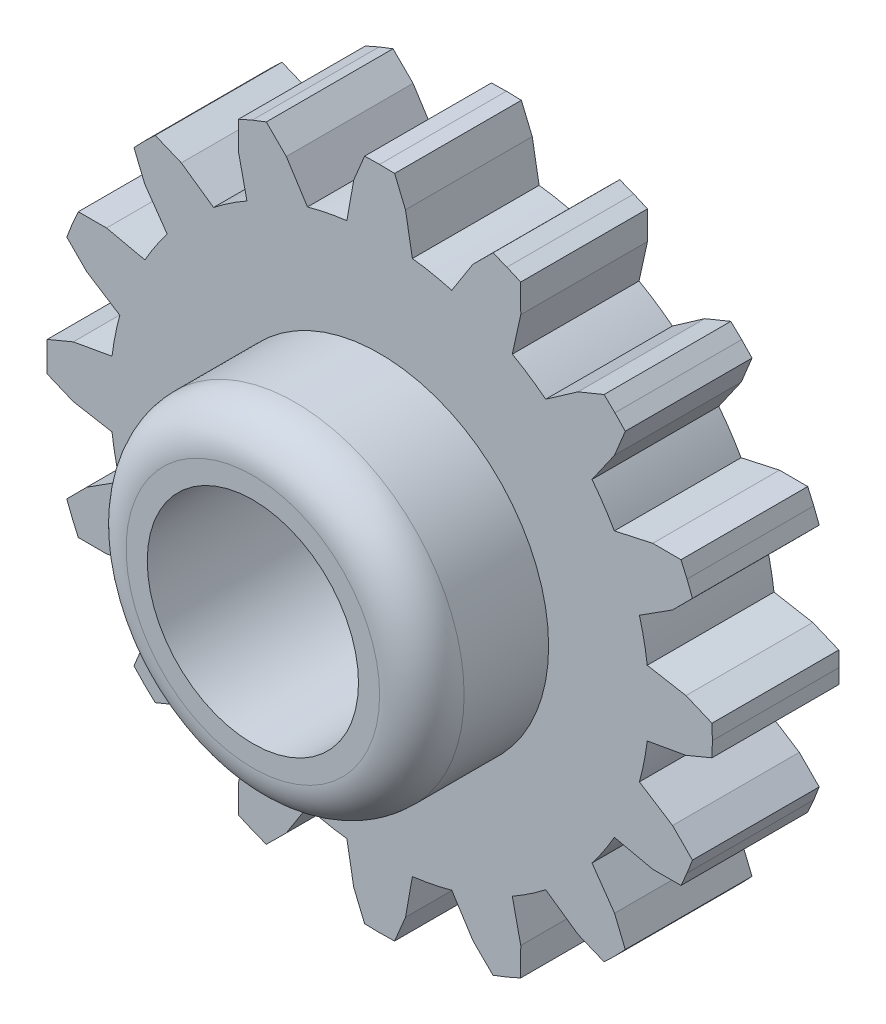
SolidWorks part; units mm, degrees
material "Chrome Stainless Steel"
ref_plane "Front Plane" through (0, 0, 0) normal (0, 0, 1) x (1, 0, 0)
ref_plane "Top Plane" through (0, 0, 0) normal (0, 1, 0) x (1, 0, 0)
ref_plane "Right Plane" through (0, 0, 0) normal (1, 0, 0) x (0, 0, -1)
sketch "Sketch1" plane through (0, 0, 0) normal (0, 0, 1) x (1, 0, 0)
  line L0 (0, 6.3811) -> (0, 7.875) construction
  line L1 (-0.7753, 6.3338) -> (-0.6124, 7.2503)
  line L2 (-0.6124, 7.2503) -> (-0.3549, 7.867)
  line L3 (-0.3549, 7.867) -> (0, 7.875)
  line L4 (0.3549, 7.867) -> (0, 7.875)
  line L5 (0.7753, 6.3338) -> (0.6124, 7.2503)
  line L6 (0.6124, 7.2503) -> (0.3549, 7.867)
  line L7 (1.7075, 6.1484) -> (2.2088, 6.9328)
  line L8 (2.2088, 6.9328) -> (2.6827, 7.404)
  line L9 (2.6827, 7.404) -> (3.0136, 7.2756)
  line L10 (3.3385, 7.1323) -> (3.0136, 7.2756)
  line L11 (3.1401, 5.555) -> (3.3403, 6.4641)
  line L12 (3.3403, 6.4641) -> (3.3385, 7.1323)
  line L13 (2.4419, 5.8954) -> (3.0136, 7.2756) construction
  line L14 (3.9305, 5.0269) -> (4.6937, 5.5598)
  line L15 (4.6937, 5.5598) -> (5.3118, 5.8138)
  line L16 (5.3118, 5.8138) -> (5.5685, 5.5685)
  line L17 (5.8138, 5.3118) -> (5.5685, 5.5685)
  line L18 (5.0269, 3.9305) -> (5.5598, 4.6937)
  line L19 (5.5598, 4.6937) -> (5.8138, 5.3118)
  line L20 (4.5121, 4.5121) -> (5.5685, 5.5685) construction
  line L21 (5.555, 3.1401) -> (6.4641, 3.3403)
  line L22 (6.4641, 3.3403) -> (7.1323, 3.3385)
  line L23 (7.1323, 3.3385) -> (7.2756, 3.0136)
  line L24 (7.404, 2.6827) -> (7.2756, 3.0136)
  line L25 (6.1484, 1.7075) -> (6.9328, 2.2088)
  line L26 (6.9328, 2.2088) -> (7.404, 2.6827)
  line L27 (5.8954, 2.4419) -> (7.2756, 3.0136) construction
  line L28 (6.3338, 0.7753) -> (7.2503, 0.6124)
  line L29 (7.2503, 0.6124) -> (7.867, 0.3549)
  line L30 (7.867, 0.3549) -> (7.875, 0)
  line L31 (7.867, -0.3549) -> (7.875, 0)
  line L32 (6.3338, -0.7753) -> (7.2503, -0.6124)
  line L33 (7.2503, -0.6124) -> (7.867, -0.3549)
  line L34 (6.3811, 0) -> (7.875, 0) construction
  line L35 (6.1484, -1.7075) -> (6.9328, -2.2088)
  line L36 (6.9328, -2.2088) -> (7.404, -2.6827)
  line L37 (7.404, -2.6827) -> (7.2756, -3.0136)
  line L38 (7.1323, -3.3385) -> (7.2756, -3.0136)
  line L39 (5.555, -3.1401) -> (6.4641, -3.3403)
  line L40 (6.4641, -3.3403) -> (7.1323, -3.3385)
  line L41 (5.8954, -2.4419) -> (7.2756, -3.0136) construction
  line L42 (5.0269, -3.9305) -> (5.5598, -4.6937)
  line L43 (5.5598, -4.6937) -> (5.8138, -5.3118)
  line L44 (5.8138, -5.3118) -> (5.5685, -5.5685)
  line L45 (5.3118, -5.8138) -> (5.5685, -5.5685)
  line L46 (3.9305, -5.0269) -> (4.6937, -5.5598)
  line L47 (4.6937, -5.5598) -> (5.3118, -5.8138)
  line L48 (4.5121, -4.5121) -> (5.5685, -5.5685) construction
  line L49 (3.1401, -5.555) -> (3.3403, -6.4641)
  line L50 (3.3403, -6.4641) -> (3.3385, -7.1323)
  line L51 (3.3385, -7.1323) -> (3.0136, -7.2756)
  line L52 (2.6827, -7.404) -> (3.0136, -7.2756)
  line L53 (1.7075, -6.1484) -> (2.2088, -6.9328)
  line L54 (2.2088, -6.9328) -> (2.6827, -7.404)
  line L55 (2.4419, -5.8954) -> (3.0136, -7.2756) construction
  line L56 (0.7753, -6.3338) -> (0.6124, -7.2503)
  line L57 (0.6124, -7.2503) -> (0.3549, -7.867)
  line L58 (0.3549, -7.867) -> (0, -7.875)
  line L59 (-0.3549, -7.867) -> (0, -7.875)
  line L60 (-0.7753, -6.3338) -> (-0.6124, -7.2503)
  line L61 (-0.6124, -7.2503) -> (-0.3549, -7.867)
  line L62 (0, -6.3811) -> (0, -7.875) construction
  line L63 (-1.7075, -6.1484) -> (-2.2088, -6.9328)
  line L64 (-2.2088, -6.9328) -> (-2.6827, -7.404)
  line L65 (-2.6827, -7.404) -> (-3.0136, -7.2756)
  line L66 (-3.3385, -7.1323) -> (-3.0136, -7.2756)
  line L67 (-3.1401, -5.555) -> (-3.3403, -6.4641)
  line L68 (-3.3403, -6.4641) -> (-3.3385, -7.1323)
  line L69 (-2.4419, -5.8954) -> (-3.0136, -7.2756) construction
  line L70 (-3.9305, -5.0269) -> (-4.6937, -5.5598)
  line L71 (-4.6937, -5.5598) -> (-5.3118, -5.8138)
  line L72 (-5.3118, -5.8138) -> (-5.5685, -5.5685)
  line L73 (-5.8138, -5.3118) -> (-5.5685, -5.5685)
  line L74 (-5.0269, -3.9305) -> (-5.5598, -4.6937)
  line L75 (-5.5598, -4.6937) -> (-5.8138, -5.3118)
  line L76 (-4.5121, -4.5121) -> (-5.5685, -5.5685) construction
  line L77 (-5.555, -3.1401) -> (-6.4641, -3.3403)
  line L78 (-6.4641, -3.3403) -> (-7.1323, -3.3385)
  line L79 (-7.1323, -3.3385) -> (-7.2756, -3.0136)
  line L80 (-7.404, -2.6827) -> (-7.2756, -3.0136)
  line L81 (-6.1484, -1.7075) -> (-6.9328, -2.2088)
  line L82 (-6.9328, -2.2088) -> (-7.404, -2.6827)
  line L83 (-5.8954, -2.4419) -> (-7.2756, -3.0136) construction
  line L84 (-6.3338, -0.7753) -> (-7.2503, -0.6124)
  line L85 (-7.2503, -0.6124) -> (-7.867, -0.3549)
  line L86 (-7.867, -0.3549) -> (-7.875, 0)
  line L87 (-7.867, 0.3549) -> (-7.875, 0)
  line L88 (-6.3338, 0.7753) -> (-7.2503, 0.6124)
  line L89 (-7.2503, 0.6124) -> (-7.867, 0.3549)
  line L90 (-6.3811, 0) -> (-7.875, 0) construction
  line L91 (-6.1484, 1.7075) -> (-6.9328, 2.2088)
  line L92 (-6.9328, 2.2088) -> (-7.404, 2.6827)
  line L93 (-7.404, 2.6827) -> (-7.2756, 3.0136)
  line L94 (-7.1323, 3.3385) -> (-7.2756, 3.0136)
  line L95 (-5.555, 3.1401) -> (-6.4641, 3.3403)
  line L96 (-6.4641, 3.3403) -> (-7.1323, 3.3385)
  line L97 (-5.8954, 2.4419) -> (-7.2756, 3.0136) construction
  line L98 (-5.0269, 3.9305) -> (-5.5598, 4.6937)
  line L99 (-5.5598, 4.6937) -> (-5.8138, 5.3118)
  line L100 (-5.8138, 5.3118) -> (-5.5685, 5.5685)
  line L101 (-5.3118, 5.8138) -> (-5.5685, 5.5685)
  line L102 (-3.9305, 5.0269) -> (-4.6937, 5.5598)
  line L103 (-4.6937, 5.5598) -> (-5.3118, 5.8138)
  line L104 (-4.5121, 4.5121) -> (-5.5685, 5.5685) construction
  line L105 (-3.1401, 5.555) -> (-3.3403, 6.4641)
  line L106 (-3.3403, 6.4641) -> (-3.3385, 7.1323)
  line L107 (-3.3385, 7.1323) -> (-3.0136, 7.2756)
  line L108 (-2.6827, 7.404) -> (-3.0136, 7.2756)
  line L109 (-1.7075, 6.1484) -> (-2.2088, 6.9328)
  line L110 (-2.2088, 6.9328) -> (-2.6827, 7.404)
  line L111 (-2.4419, 5.8954) -> (-3.0136, 7.2756) construction
  circle A0 centre (0, 0) radius 6.3811
  circle A1 centre (0, 0) radius 7.875
  circle A2 centre (0, 0) radius 2.5
  point P135 (0, 0)
  point P166 (0, 0)
  point P246 (0, 0)
  dimension "D1" = 15.75
  dimension "D2" = 5
  dimension "D3" = 0.3549
  dimension "D4" = 0.6682
  dimension "D5" = 3.0136
  dimension "D6" = 1.6277
  dimension "D8" = 0.9309
  dimension "D9" = 167.42
  dimension "D10" = 42.661
  dimension "D7" = 16
extrude "Boss-Extrude3" add sketch "Sketch1" along normal blind 3 contours A0 | A0 L11 L12 L10 L9 L8 L7 | A0 L5 L6 L4 L3 L2 L1 | A0 L109 L110 L108 L107 L106 L105 | A0 L102 L103 L101 L100 L99 L98 | A0 L95 L96 L94 L93 L92 L91 | A0 L88 L89 L87 L86 L85 L84 | A0 L81 L82 L80 L79 L78 L77 | A0 L74 L75 L73 L72 L71 L70 | A0 L67 L68 L66 L65 L64 L63 | A0 L60 L61 L59 L58 L57 L56 | A0 L53 L54 L52 L51 L50 L49 | A0 L46 L47 L45 L44 L43 L42 | A0 L39 L40 L38 L37 L36 L35 | A0 L32 L33 L31 L30 L29 L28 | A0 L25 L26 L24 L23 L22 L21 | A0 L18 L19 L17 L16 L15 L14
sketch "Sketch4" plane through (0, 0, 3) normal (0, 0, 1) x (1, 0, 0)
  line L96 (6.1484, 1.7075) -> (6.9328, 2.2088)
  line L97 (6.9328, 2.2088) -> (7.404, 2.6827)
  line L98 (7.404, 2.6827) -> (7.2756, 3.0136)
  line L99 (7.2756, 3.0136) -> (7.1323, 3.3385)
  line L100 (7.1323, 3.3385) -> (6.4641, 3.3403)
  line L101 (6.4641, 3.3403) -> (5.555, 3.1401)
  line L102 (5.0269, 3.9305) -> (5.5598, 4.6937)
  line L103 (5.5598, 4.6937) -> (5.8138, 5.3118)
  line L104 (5.8138, 5.3118) -> (5.5685, 5.5685)
  line L105 (5.5685, 5.5685) -> (5.3118, 5.8138)
  line L106 (5.3118, 5.8138) -> (4.6937, 5.5598)
  line L107 (4.6937, 5.5598) -> (3.9305, 5.0269)
  line L108 (3.1401, 5.555) -> (3.3403, 6.4641)
  line L109 (3.3403, 6.4641) -> (3.3385, 7.1323)
  line L110 (3.3385, 7.1323) -> (3.0136, 7.2756)
  line L111 (3.0136, 7.2756) -> (2.6827, 7.404)
  line L112 (2.6827, 7.404) -> (2.2088, 6.9328)
  line L113 (2.2088, 6.9328) -> (1.7075, 6.1484)
  line L114 (0.7753, 6.3338) -> (0.6124, 7.2503)
  line L115 (0.6124, 7.2503) -> (0.3549, 7.867)
  line L116 (0.3549, 7.867) -> (0, 7.875)
  line L117 (0, 7.875) -> (-0.3549, 7.867)
  line L118 (-0.3549, 7.867) -> (-0.6124, 7.2503)
  line L119 (-0.6124, 7.2503) -> (-0.7753, 6.3338)
  line L120 (-1.7075, 6.1484) -> (-2.2088, 6.9328)
  line L121 (-2.2088, 6.9328) -> (-2.6827, 7.404)
  line L122 (-2.6827, 7.404) -> (-3.0136, 7.2756)
  line L123 (-3.0136, 7.2756) -> (-3.3385, 7.1323)
  line L124 (-3.3385, 7.1323) -> (-3.3403, 6.4641)
  line L125 (-3.3403, 6.4641) -> (-3.1401, 5.555)
  line L126 (-3.9305, 5.0269) -> (-4.6937, 5.5598)
  line L127 (-4.6937, 5.5598) -> (-5.3118, 5.8138)
  line L128 (-5.3118, 5.8138) -> (-5.5685, 5.5685)
  line L129 (-5.5685, 5.5685) -> (-5.8138, 5.3118)
  line L130 (-5.8138, 5.3118) -> (-5.5598, 4.6937)
  line L131 (-5.5598, 4.6937) -> (-5.0269, 3.9305)
  line L132 (-5.555, 3.1401) -> (-6.4641, 3.3403)
  line L133 (-6.4641, 3.3403) -> (-7.1323, 3.3385)
  line L134 (-7.1323, 3.3385) -> (-7.2756, 3.0136)
  line L135 (-7.2756, 3.0136) -> (-7.404, 2.6827)
  line L136 (-7.404, 2.6827) -> (-6.9328, 2.2088)
  line L137 (-6.9328, 2.2088) -> (-6.1484, 1.7075)
  line L138 (-6.3338, 0.7753) -> (-7.2503, 0.6124)
  line L139 (-7.2503, 0.6124) -> (-7.867, 0.3549)
  line L140 (-7.867, 0.3549) -> (-7.875, 0)
  line L141 (-7.875, 0) -> (-7.867, -0.3549)
  line L142 (-7.867, -0.3549) -> (-7.2503, -0.6124)
  line L143 (-7.2503, -0.6124) -> (-6.3338, -0.7753)
  line L144 (-6.1484, -1.7075) -> (-6.9328, -2.2088)
  line L145 (-6.9328, -2.2088) -> (-7.404, -2.6827)
  line L146 (-7.404, -2.6827) -> (-7.2756, -3.0136)
  line L147 (-7.2756, -3.0136) -> (-7.1323, -3.3385)
  line L148 (-7.1323, -3.3385) -> (-6.4641, -3.3403)
  line L149 (-6.4641, -3.3403) -> (-5.555, -3.1401)
  line L150 (-5.0269, -3.9305) -> (-5.5598, -4.6937)
  line L151 (-5.5598, -4.6937) -> (-5.8138, -5.3118)
  line L152 (-5.8138, -5.3118) -> (-5.5685, -5.5685)
  line L153 (-5.5685, -5.5685) -> (-5.3118, -5.8138)
  line L154 (-5.3118, -5.8138) -> (-4.6937, -5.5598)
  line L155 (-4.6937, -5.5598) -> (-3.9305, -5.0269)
  line L156 (-3.1401, -5.555) -> (-3.3403, -6.4641)
  line L157 (-3.3403, -6.4641) -> (-3.3385, -7.1323)
  line L158 (-3.3385, -7.1323) -> (-3.0136, -7.2756)
  line L159 (-3.0136, -7.2756) -> (-2.6827, -7.404)
  line L160 (-2.6827, -7.404) -> (-2.2088, -6.9328)
  line L161 (-2.2088, -6.9328) -> (-1.7075, -6.1484)
  line L162 (-0.7753, -6.3338) -> (-0.6124, -7.2503)
  line L163 (-0.6124, -7.2503) -> (-0.3549, -7.867)
  line L164 (-0.3549, -7.867) -> (0, -7.875)
  line L165 (0, -7.875) -> (0.3549, -7.867)
  line L166 (0.3549, -7.867) -> (0.6124, -7.2503)
  line L167 (0.6124, -7.2503) -> (0.7753, -6.3338)
  line L168 (1.7075, -6.1484) -> (2.2088, -6.9328)
  line L169 (2.2088, -6.9328) -> (2.6827, -7.404)
  line L170 (2.6827, -7.404) -> (3.0136, -7.2756)
  line L171 (3.0136, -7.2756) -> (3.3385, -7.1323)
  line L172 (3.3385, -7.1323) -> (3.3403, -6.4641)
  line L173 (3.3403, -6.4641) -> (3.1401, -5.555)
  line L174 (3.9305, -5.0269) -> (4.6937, -5.5598)
  line L175 (4.6937, -5.5598) -> (5.3118, -5.8138)
  line L176 (5.3118, -5.8138) -> (5.5685, -5.5685)
  line L177 (5.5685, -5.5685) -> (5.8138, -5.3118)
  line L178 (5.8138, -5.3118) -> (5.5598, -4.6937)
  line L179 (5.5598, -4.6937) -> (5.0269, -3.9305)
  line L180 (5.555, -3.1401) -> (6.4641, -3.3403)
  line L181 (6.4641, -3.3403) -> (7.1323, -3.3385)
  line L182 (7.1323, -3.3385) -> (7.2756, -3.0136)
  line L183 (7.2756, -3.0136) -> (7.404, -2.6827)
  line L184 (7.404, -2.6827) -> (6.9328, -2.2088)
  line L185 (6.9328, -2.2088) -> (6.1484, -1.7075)
  line L186 (6.3338, -0.7753) -> (7.2503, -0.6124)
  line L187 (7.2503, -0.6124) -> (7.867, -0.3549)
  line L188 (7.867, -0.3549) -> (7.875, 0)
  line L189 (7.875, 0) -> (7.867, 0.3549)
  line L190 (7.867, 0.3549) -> (7.2503, 0.6124)
  line L191 (7.2503, 0.6124) -> (6.3338, 0.7753)
  line L192 (6.1484, 1.7075) -> (6.9328, 2.2088)
  line L193 (6.9328, 2.2088) -> (7.404, 2.6827)
  line L194 (7.404, 2.6827) -> (7.2756, 3.0136)
  line L195 (7.2756, 3.0136) -> (7.1323, 3.3385)
  line L196 (7.1323, 3.3385) -> (6.4641, 3.3403)
  line L197 (6.4641, 3.3403) -> (5.555, 3.1401)
  line L198 (5.0269, 3.9305) -> (5.5598, 4.6937)
  line L199 (5.5598, 4.6937) -> (5.8138, 5.3118)
  line L200 (5.8138, 5.3118) -> (5.5685, 5.5685)
  line L201 (5.5685, 5.5685) -> (5.3118, 5.8138)
  line L202 (5.3118, 5.8138) -> (4.6937, 5.5598)
  line L203 (4.6937, 5.5598) -> (3.9305, 5.0269)
  line L204 (3.1401, 5.555) -> (3.3403, 6.4641)
  line L205 (3.3403, 6.4641) -> (3.3385, 7.1323)
  line L206 (3.3385, 7.1323) -> (3.0136, 7.2756)
  line L207 (3.0136, 7.2756) -> (2.6827, 7.404)
  line L208 (2.6827, 7.404) -> (2.2088, 6.9328)
  line L209 (2.2088, 6.9328) -> (1.7075, 6.1484)
  line L210 (0.7753, 6.3338) -> (0.6124, 7.2503)
  line L211 (0.6124, 7.2503) -> (0.3549, 7.867)
  line L212 (0.3549, 7.867) -> (0, 7.875)
  line L213 (0, 7.875) -> (-0.3549, 7.867)
  line L214 (-0.3549, 7.867) -> (-0.6124, 7.2503)
  line L215 (-0.6124, 7.2503) -> (-0.7753, 6.3338)
  line L216 (-1.7075, 6.1484) -> (-2.2088, 6.9328)
  line L217 (-2.2088, 6.9328) -> (-2.6827, 7.404)
  line L218 (-2.6827, 7.404) -> (-3.0136, 7.2756)
  line L219 (-3.0136, 7.2756) -> (-3.3385, 7.1323)
  line L220 (-3.3385, 7.1323) -> (-3.3403, 6.4641)
  line L221 (-3.3403, 6.4641) -> (-3.1401, 5.555)
  line L222 (-3.9305, 5.0269) -> (-4.6937, 5.5598)
  line L223 (-4.6937, 5.5598) -> (-5.3118, 5.8138)
  line L224 (-5.3118, 5.8138) -> (-5.5685, 5.5685)
  line L225 (-5.5685, 5.5685) -> (-5.8138, 5.3118)
  line L226 (-5.8138, 5.3118) -> (-5.5598, 4.6937)
  line L227 (-5.5598, 4.6937) -> (-5.0269, 3.9305)
  line L228 (-5.555, 3.1401) -> (-6.4641, 3.3403)
  line L229 (-6.4641, 3.3403) -> (-7.1323, 3.3385)
  line L230 (-7.1323, 3.3385) -> (-7.2756, 3.0136)
  line L231 (-7.2756, 3.0136) -> (-7.404, 2.6827)
  line L232 (-7.404, 2.6827) -> (-6.9328, 2.2088)
  line L233 (-6.9328, 2.2088) -> (-6.1484, 1.7075)
  line L234 (-6.3338, 0.7753) -> (-7.2503, 0.6124)
  line L235 (-7.2503, 0.6124) -> (-7.867, 0.3549)
  line L236 (-7.867, 0.3549) -> (-7.875, 0)
  line L237 (-7.875, 0) -> (-7.867, -0.3549)
  line L238 (-7.867, -0.3549) -> (-7.2503, -0.6124)
  line L239 (-7.2503, -0.6124) -> (-6.3338, -0.7753)
  line L240 (-6.1484, -1.7075) -> (-6.9328, -2.2088)
  line L241 (-6.9328, -2.2088) -> (-7.404, -2.6827)
  line L242 (-7.404, -2.6827) -> (-7.2756, -3.0136)
  line L243 (-7.2756, -3.0136) -> (-7.1323, -3.3385)
  line L244 (-7.1323, -3.3385) -> (-6.4641, -3.3403)
  line L245 (-6.4641, -3.3403) -> (-5.555, -3.1401)
  line L246 (-5.0269, -3.9305) -> (-5.5598, -4.6937)
  line L247 (-5.5598, -4.6937) -> (-5.8138, -5.3118)
  line L248 (-5.8138, -5.3118) -> (-5.5685, -5.5685)
  line L249 (-5.5685, -5.5685) -> (-5.3118, -5.8138)
  line L250 (-5.3118, -5.8138) -> (-4.6937, -5.5598)
  line L251 (-4.6937, -5.5598) -> (-3.9305, -5.0269)
  line L252 (-3.1401, -5.555) -> (-3.3403, -6.4641)
  line L253 (-3.3403, -6.4641) -> (-3.3385, -7.1323)
  line L254 (-3.3385, -7.1323) -> (-3.0136, -7.2756)
  line L255 (-3.0136, -7.2756) -> (-2.6827, -7.404)
  line L256 (-2.6827, -7.404) -> (-2.2088, -6.9328)
  line L257 (-2.2088, -6.9328) -> (-1.7075, -6.1484)
  line L258 (-0.7753, -6.3338) -> (-0.6124, -7.2503)
  line L259 (-0.6124, -7.2503) -> (-0.3549, -7.867)
  line L260 (-0.3549, -7.867) -> (0, -7.875)
  line L261 (0, -7.875) -> (0.3549, -7.867)
  line L262 (0.3549, -7.867) -> (0.6124, -7.2503)
  line L263 (0.6124, -7.2503) -> (0.7753, -6.3338)
  line L264 (1.7075, -6.1484) -> (2.2088, -6.9328)
  line L265 (2.2088, -6.9328) -> (2.6827, -7.404)
  line L266 (2.6827, -7.404) -> (3.0136, -7.2756)
  line L267 (3.0136, -7.2756) -> (3.3385, -7.1323)
  line L268 (3.3385, -7.1323) -> (3.3403, -6.4641)
  line L269 (3.3403, -6.4641) -> (3.1401, -5.555)
  line L270 (3.9305, -5.0269) -> (4.6937, -5.5598)
  line L271 (4.6937, -5.5598) -> (5.3118, -5.8138)
  line L272 (5.3118, -5.8138) -> (5.5685, -5.5685)
  line L273 (5.5685, -5.5685) -> (5.8138, -5.3118)
  line L274 (5.8138, -5.3118) -> (5.5598, -4.6937)
  line L275 (5.5598, -4.6937) -> (5.0269, -3.9305)
  line L276 (5.555, -3.1401) -> (6.4641, -3.3403)
  line L277 (6.4641, -3.3403) -> (7.1323, -3.3385)
  line L278 (7.1323, -3.3385) -> (7.2756, -3.0136)
  line L279 (7.2756, -3.0136) -> (7.404, -2.6827)
  line L280 (7.404, -2.6827) -> (6.9328, -2.2088)
  line L281 (6.9328, -2.2088) -> (6.1484, -1.7075)
  line L282 (6.3338, -0.7753) -> (7.2503, -0.6124)
  line L283 (7.2503, -0.6124) -> (7.867, -0.3549)
  line L284 (7.867, -0.3549) -> (7.875, 0)
  line L285 (7.875, 0) -> (7.867, 0.3549)
  line L286 (7.867, 0.3549) -> (7.2503, 0.6124)
  line L287 (7.2503, 0.6124) -> (6.3338, 0.7753)
  circle A0 centre (0, 0) radius 4
  circle A1 centre (0, 0) radius 2.5
  arc A17 (6.3338, 0.7753) -> (6.1484, 1.7075) centre (0, 0) ccw
  arc A18 (5.555, 3.1401) -> (5.0269, 3.9305) centre (0, 0) ccw
  arc A19 (3.9305, 5.0269) -> (3.1401, 5.555) centre (0, 0) ccw
  arc A20 (1.7075, 6.1484) -> (0.7753, 6.3338) centre (0, 0) ccw
  arc A21 (-0.7753, 6.3338) -> (-1.7075, 6.1484) centre (0, 0) ccw
  arc A22 (-3.1401, 5.555) -> (-3.9305, 5.0269) centre (0, 0) ccw
  arc A23 (-5.0269, 3.9305) -> (-5.555, 3.1401) centre (0, 0) ccw
  arc A24 (-6.1484, 1.7075) -> (-6.3338, 0.7753) centre (0, 0) ccw
  arc A25 (-6.3338, -0.7753) -> (-6.1484, -1.7075) centre (0, 0) ccw
  arc A26 (-5.555, -3.1401) -> (-5.0269, -3.9305) centre (0, 0) ccw
  arc A27 (-3.9305, -5.0269) -> (-3.1401, -5.555) centre (0, 0) ccw
  arc A28 (-1.7075, -6.1484) -> (-0.7753, -6.3338) centre (0, 0) ccw
  arc A29 (0.7753, -6.3338) -> (1.7075, -6.1484) centre (0, 0) ccw
  arc A30 (3.1401, -5.555) -> (3.9305, -5.0269) centre (0, 0) ccw
  arc A31 (5.0269, -3.9305) -> (5.555, -3.1401) centre (0, 0) ccw
  arc A32 (6.1484, -1.7075) -> (6.3338, -0.7753) centre (0, 0) ccw
  arc A33 (6.3338, 0.7753) -> (6.1484, 1.7075) centre (0, 0) ccw
  arc A34 (5.555, 3.1401) -> (5.0269, 3.9305) centre (0, 0) ccw
  arc A35 (3.9305, 5.0269) -> (3.1401, 5.555) centre (0, 0) ccw
  arc A36 (1.7075, 6.1484) -> (0.7753, 6.3338) centre (0, 0) ccw
  arc A37 (-0.7753, 6.3338) -> (-1.7075, 6.1484) centre (0, 0) ccw
  arc A38 (-3.1401, 5.555) -> (-3.9305, 5.0269) centre (0, 0) ccw
  arc A39 (-5.0269, 3.9305) -> (-5.555, 3.1401) centre (0, 0) ccw
  arc A40 (-6.1484, 1.7075) -> (-6.3338, 0.7753) centre (0, 0) ccw
  arc A41 (-6.3338, -0.7753) -> (-6.1484, -1.7075) centre (0, 0) ccw
  arc A42 (-5.555, -3.1401) -> (-5.0269, -3.9305) centre (0, 0) ccw
  arc A43 (-3.9305, -5.0269) -> (-3.1401, -5.555) centre (0, 0) ccw
  arc A44 (-1.7075, -6.1484) -> (-0.7753, -6.3338) centre (0, 0) ccw
  arc A45 (0.7753, -6.3338) -> (1.7075, -6.1484) centre (0, 0) ccw
  arc A46 (3.1401, -5.555) -> (3.9305, -5.0269) centre (0, 0) ccw
  arc A47 (5.0269, -3.9305) -> (5.555, -3.1401) centre (0, 0) ccw
  arc A48 (6.1484, -1.7075) -> (6.3338, -0.7753) centre (0, 0) ccw
  dimension "D1" = 8
  dimension "D2" = 0
extrude "Boss-Extrude4" add sketch "Sketch4" along normal blind 3 contours A0 A1
fillet "Fillet1" radius 1 1 edges at (4, 0, 6)
fillet "Fillet2" radius 0.25 1 edges at (2.5, 0, 0)
